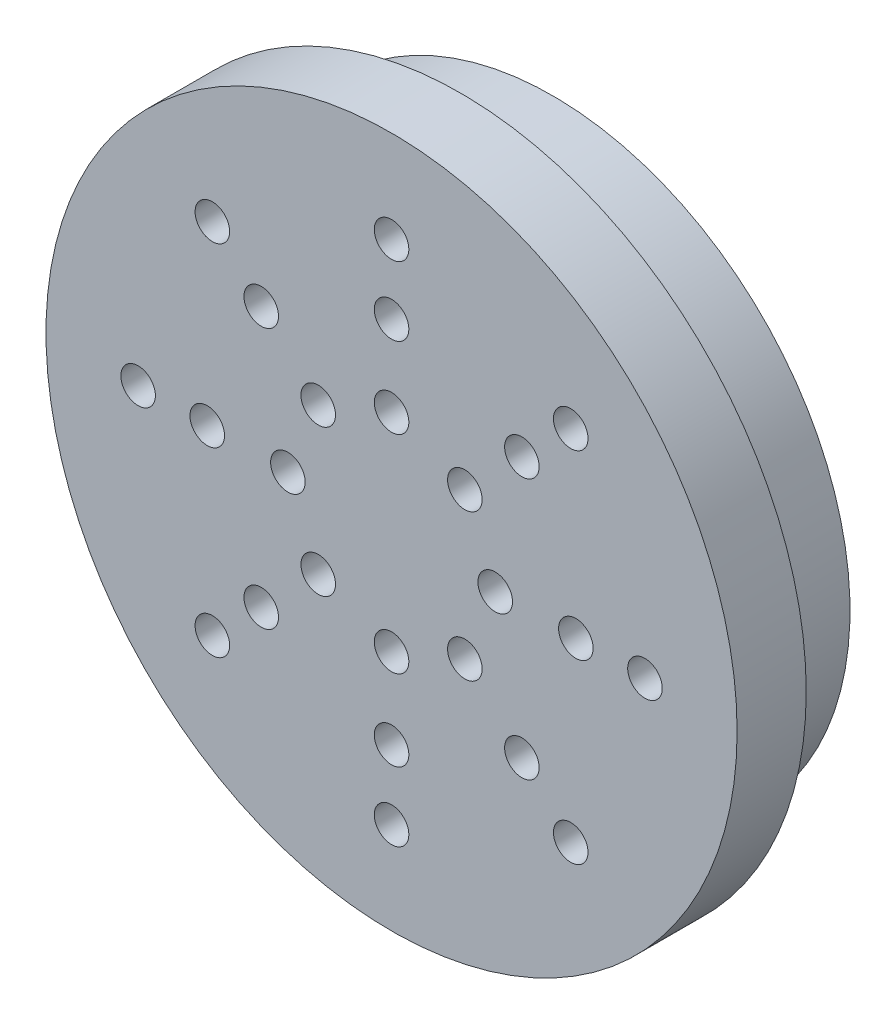
SolidWorks part; units mm, degrees
ref_plane "Front Plane" through (0, 0, 0) normal (0, 0, 1) x (1, 0, 0)
ref_plane "Top Plane" through (0, 0, 0) normal (0, 1, 0) x (1, 0, 0)
ref_plane "Right Plane" through (0, 0, 0) normal (1, 0, 0) x (0, 0, -1)
sketch "Sketch2" plane through (0, 0, 0) normal (0, 0, 1) x (1, 0, 0)
  circle A0 centre (0, 0) radius 15
extrude "Boss-Extrude1" add sketch "Sketch2" along normal blind 3
sketch "Sketch3" plane through (0, 0, 0) normal (0, 0, -1) x (-1, 0, 0)
  circle A0 centre (0, 0) radius 13 construction
  circle A1 centre (0, 0) radius 13 construction
  circle A2 centre (0, 0) radius 12.9
  dimension "D1" = 0.1
extrude "Boss-Extrude2" add sketch "Sketch3" along normal blind 4
sketch "Sketch4" plane through (0, 0, 3) normal (0, 0, 1) x (1, 0, 0)
  line L0 (-15, 0) -> (15, 0) construction
  circle A0 centre (0, 0) radius 15 construction
  circle A1 centre (-4.5, 0) radius 0.75
  circle A2 centre (-8, 0) radius 0.75
  circle A3 centre (-11, 0) radius 0.75
  circle A4 centre (-3.182, 3.182) radius 0.75
  circle A5 centre (-5.6569, 5.6569) radius 0.75
  circle A6 centre (-7.7782, 7.7782) radius 0.75
  circle A7 centre (0, 4.5) radius 0.75
  circle A8 centre (0, 8) radius 0.75
  circle A9 centre (0, 11) radius 0.75
  circle A10 centre (3.182, 3.182) radius 0.75
  circle A11 centre (5.6569, 5.6569) radius 0.75
  circle A12 centre (7.7782, 7.7782) radius 0.75
  circle A13 centre (4.5, 0) radius 0.75
  circle A14 centre (8, 0) radius 0.75
  circle A15 centre (11, 0) radius 0.75
  circle A16 centre (3.182, -3.182) radius 0.75
  circle A17 centre (5.6569, -5.6569) radius 0.75
  circle A18 centre (7.7782, -7.7782) radius 0.75
  circle A19 centre (0, -4.5) radius 0.75
  circle A20 centre (0, -8) radius 0.75
  circle A21 centre (0, -11) radius 0.75
  circle A22 centre (-3.182, -3.182) radius 0.75
  circle A23 centre (-5.6569, -5.6569) radius 0.75
  circle A24 centre (-7.7782, -7.7782) radius 0.75
  point P57 (0, 0)
  dimension "D4" = 1.5
  dimension "D5" = 1.5
  dimension "D6" = 1.5
  dimension "D1" = 4.5
  dimension "D2" = 3.5
  dimension "D3" = 3
  dimension "D7" = 8
extrude "Cut-Extrude1" cut sketch "Sketch4" against normal through all
